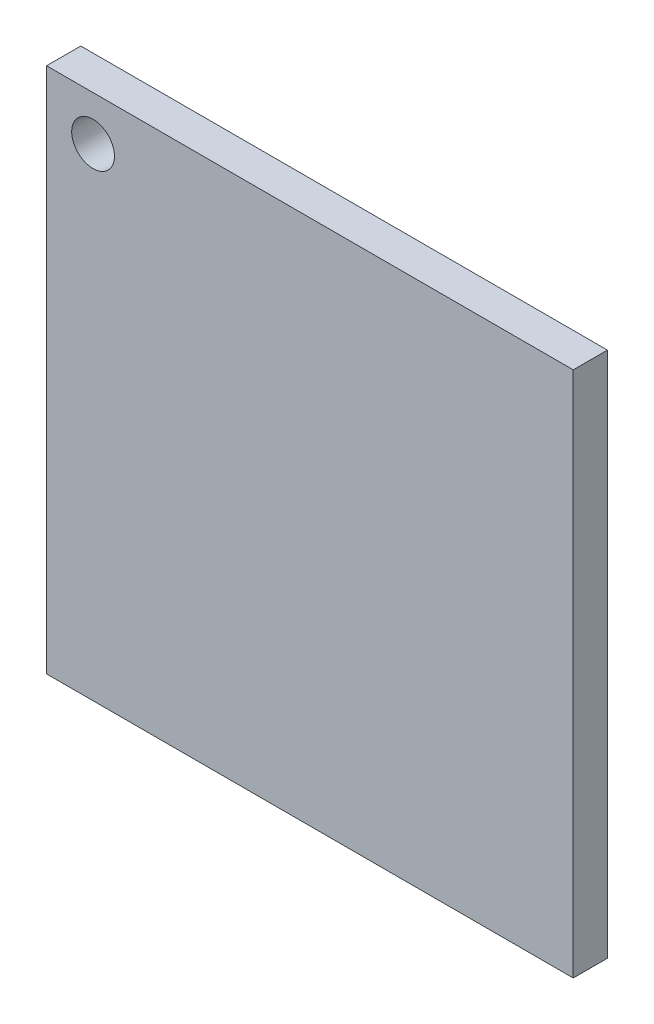
SolidWorks part; units mm, degrees
ref_plane "Front Plane" through (0, 0, 0) normal (0, 0, 1) x (1, 0, 0)
ref_plane "Top Plane" through (0, 0, 0) normal (0, 1, 0) x (1, 0, 0)
ref_plane "Right Plane" through (0, 0, 0) normal (1, 0, 0) x (0, 0, -1)
sketch "Sketch1" plane through (0, 0, 0) normal (0, 0, 1) x (1, 0, 0)
  line L0 (0, -13) -> (13.6, -13) construction
  line L1 (0, 0) -> (154, 0)
  line L2 (0, 0) -> (0, -154)
  line L3 (0, -154) -> (154, -154)
  line L4 (154, 0) -> (154, -154)
  line L5 (13.6, -13) -> (13.6, 0) construction
  circle A0 centre (13.6, -13) radius 6.25
  dimension "D3" = 12.5
  dimension "D1" = 154
  dimension "D2" = 13.6
  dimension "D4" = 13
extrude "Boss-Extrude1" add sketch "Sketch1" along normal blind 10 contours A0 | L1 L4 L3 L2
